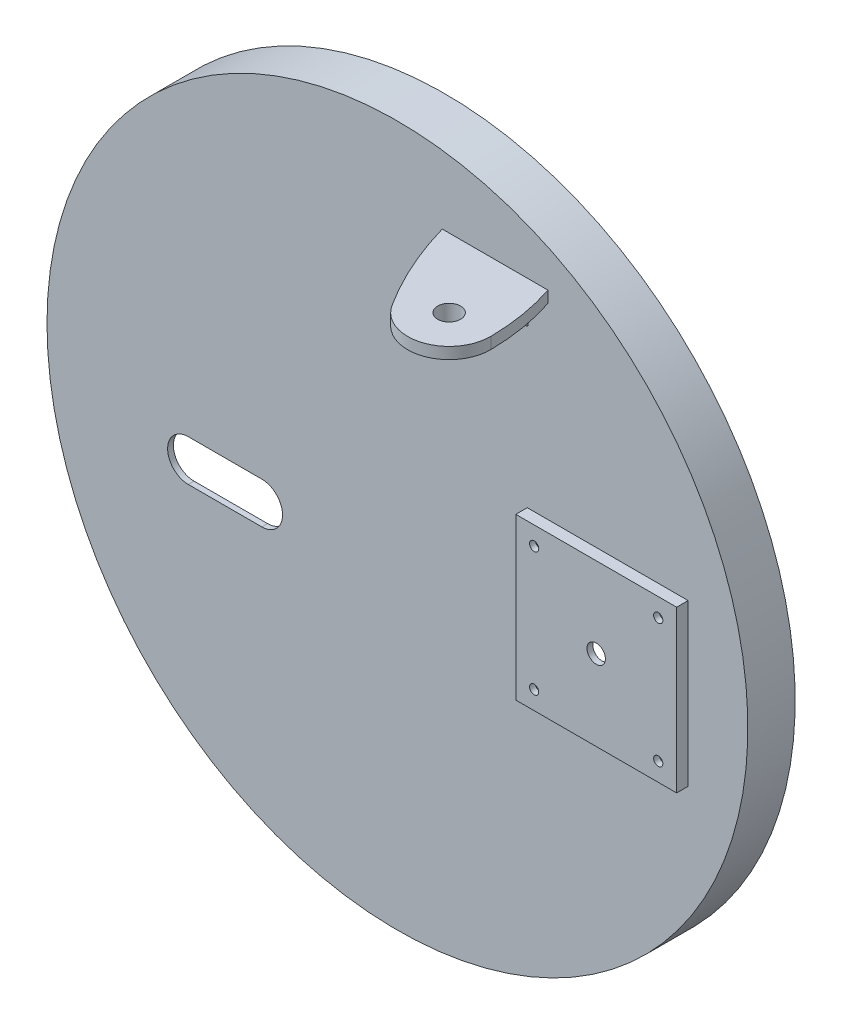
SolidWorks part; units mm, degrees
ref_plane "前视基准面" through (0, 0, 0) normal (0, 0, 1) x (1, 0, 0)
ref_plane "上视基准面" through (0, 0, 0) normal (0, 1, 0) x (1, 0, 0)
ref_plane "右视基准面" through (0, 0, 0) normal (1, 0, 0) x (0, 0, -1)
sketch "草图1" plane through (0, 0, 0) normal (0, 0, 1) x (1, 0, 0)
  line L0 (-466.0859, 0) -> (425.9445, 0) construction
  line L1 (0, -434.8648) -> (0, 385.8032) construction
  circle A0 centre (0, 0) radius 305
  dimension "D1" = 610
extrude "凸台-拉伸1" add sketch "草图1" along normal blind 41.2
sketch "草图2" plane through (0, 0, 41.2) normal (0, 0, 1) x (1, 0, 0)
  line L0 (-246.6017, 0) -> (612.6017, 0) construction
  line L1 (113, 70) -> (253, 70)
  line L2 (113, 70) -> (113, -70)
  line L3 (113, -70) -> (253, -70)
  line L4 (253, 70) -> (253, -70)
  line L5 (113, 70) -> (253, -70) construction
  line L6 (113, -70) -> (253, 70) construction
  line L7 (0, -334.0404) -> (0, 391.2443) construction
  point P0 (183, 0)
  point P11 (0, 0)
  point P12 (183, 0)
  dimension "D1" = 140
  dimension "D2" = 113
  dimension "D3" = 0
  dimension "D4" = 90
extrude "凸台-拉伸2" add sketch "草图2" along normal blind 10
shell "抽壳1" thickness 5
sketch "草图3" plane through (0, 0, 41.2) normal (0, 0, 1) x (1, 0, 0)
  line L0 (-182, -42) -> (-118, -42) construction
  line L1 (-182, -24) -> (-118, -24)
  line L2 (-182, -60) -> (-118, -60)
  line L3 (113, -70) -> (253, -70) construction
  arc A0 (-182, -24) -> (-182, -60) centre (-182, -42) ccw
  arc A1 (-118, -60) -> (-118, -24) centre (-118, -42) ccw
  point P2 (-150, -42)
  point P9 (-100, -42)
  point P10 (-200, -42)
  dimension "D1" = 100
  dimension "D2" = 36
  dimension "D3" = 42
  dimension "D4" = 100
extrude "切除-拉伸1" cut sketch "草图3" against normal blind 10
sketch "草图4" plane through (0, 0, 41.2) normal (0, 0, 1) x (1, 0, 0)
  line L1 (39, 243) -> (159, 243)
  line L2 (39, 243) -> (39, 233)
  line L3 (39, 233) -> (159, 233)
  line L4 (159, 243) -> (159, 233)
  dimension "D1" = 39
  dimension "D2" = 243
  dimension "D3" = 10
  dimension "D4" = 120
extrude "凸台-拉伸3" add sketch "草图4" along normal blind 150
sketch "草图6" plane through (0, 233, 0) normal (0, -1, 0) x (1, 0, 0)
  line L1 (39, 41.2) -> (159, 41.2) construction
  line L2 (305, 41.2) -> (-305, 41.2) construction
  line L3 (39, 41.2) -> (131, 41.2)
  line L4 (159, 41.2) -> (159, 191.2)
  line L5 (159, 191.2) -> (159, 41.2) construction
  line L6 (159, 191.2) -> (39, 191.2)
  line L7 (39, 191.2) -> (39, 41.2)
  arc A0 (39, 41.2) -> (74.6468, 120.5567) centre (327.5902, -40.7493) cw
  arc A1 (74.6468, 120.5567) -> (140.998, 100.8218) centre (105, 101.2) cw
  arc A2 (140.998, 100.8218) -> (131, 41.2) centre (-53.9912, 102.8705) cw
  line M1 (39, 41.2) -> (159, 41.2)
  line M2 (159, 41.2) -> (159, 191.2)
  line M3 (159, 191.2) -> (39, 191.2)
  line M4 (39, 191.2) -> (39, 41.2)
  dimension "D2" = 300
  dimension "D3" = 36
  dimension "D4" = 195
  dimension "D1" = 105
  dimension "D5" = 60
  dimension "D6" = 92
extrude "切除-拉伸2" cut sketch "草图6" against normal through all contours A1 A2 A0 M1 M2 M3 M4
sketch "草图7" plane through (0, 233, 0) normal (0, -1, 0) x (1, 0, 0)
  circle A0 centre (105, 101.2) radius 10
  dimension "D1" = 20
extrude "切除-拉伸3" cut sketch "草图7" against normal blind 150
sketch "草图8" plane through (0, 233, 0) normal (0, -1, 0) x (1, 0, 0)
  circle A0 centre (105, 101.2) radius 20
  circle A1 centre (105, 101.2) radius 10 construction
  circle A2 centre (105, 101.2) radius 10
  dimension "D1" = 40
extrude "凸台-拉伸4" add sketch "草图8" along normal blind 10
sketch "草图9" plane through (0, 233, 0) normal (0, -1, 0) x (1, 0, 0)
  line L0 (305, 41.2) -> (-305, 41.2) construction
  line L1 (77.5, 41.2) -> (72.5, 41.2)
  line L2 (77.5, 41.2) -> (77.5, 77.2)
  line L3 (77.5, 77.2) -> (72.5, 77.2)
  line L4 (72.5, 41.2) -> (72.5, 77.2)
  line L5 (39, 41.2) -> (131, 41.2) construction
  line L6 (108.5, 41.2) -> (113.5, 41.2)
  line L7 (108.5, 41.2) -> (108.5, 77.2)
  line L8 (108.5, 77.2) -> (113.5, 77.2)
  line L9 (113.5, 41.2) -> (113.5, 77.2)
  point P12 (0, 0)
  point P14 (75, 41.2)
  point P15 (111, 41.2)
  point P18 (72.355, 41.2)
  dimension "D1" = 75
  dimension "D2" = 36
  dimension "D3" = 5
  dimension "D4" = 36
extrude "凸台-拉伸5" add sketch "草图9" along normal blind 26
sketch "草图10" plane through (72.5, 0, 0) normal (-1, 0, 0) x (0, 0, 1)
  line L0 (77.2, 233) -> (41.2, 207)
  line L1 (77.2, 207) -> (41.2, 207) construction
  line L2 (41.2, -305) -> (41.2, 305) construction
  line L3 (41.2, 207) -> (77.2, 207)
  line L4 (77.2, 207) -> (77.2, 233)
extrude "切除-拉伸4" cut sketch "草图10" against normal through all
sketch "草图11" plane through (0, 0, 0) normal (0, 1, 0) x (1, 0, 0)
  line L0 (-57, -36.2) -> (-57, -31.2)
  line L1 (-57, -31.2) -> (-75, -31.2)
  line L2 (-75, -31.2) -> (-75, -36.2)
  line L3 (-75, -36.2) -> (-57, -36.2)
  line L4 (-80, -36.2) -> (-80, 10.3)
  line L5 (-80, 10.3) -> (-85, 10.3)
  line L6 (-85, 10.3) -> (-85, -36.2)
  line L7 (-85, -36.2) -> (-80, -36.2)
  line L8 (-305, -41.2) -> (305, -41.2) construction
  line L9 (0, 0) -> (0, 55.2982) construction
  dimension "D1" = 5
  dimension "D2" = 5
  dimension "D3" = 18
  dimension "D4" = 5
  dimension "D5" = 75
  dimension "D6" = 85
  dimension "D7" = 51.5
revolve "旋转1" add sketch "草图11" angle 360 about L9
sketch "草图12" plane through (0, 0, 51.2) normal (0, 0, 1) x (1, 0, 0)
  line L8 (129, 54) -> (129, -54)
  line L9 (129, -54) -> (237, -54)
  line L10 (237, -54) -> (237, 54)
  line L11 (237, 54) -> (129, 54)
  line L12 (129, 54) -> (129, -54) construction
  line L13 (129, -54) -> (237, -54) construction
  line L14 (237, -54) -> (237, 54) construction
  line L15 (237, 54) -> (129, 54) construction
  circle A0 centre (237, 54) radius 4
  circle A1 centre (237, -54) radius 4
  circle A2 centre (129, -54) radius 4
  circle A3 centre (129, 54) radius 4
  circle A4 centre (183, 0) radius 8
  dimension "D2" = 16
  dimension "D3" = 8
  dimension "D1" = 16
extrude "切除-拉伸5" cut sketch "草图12" against normal blind 26
